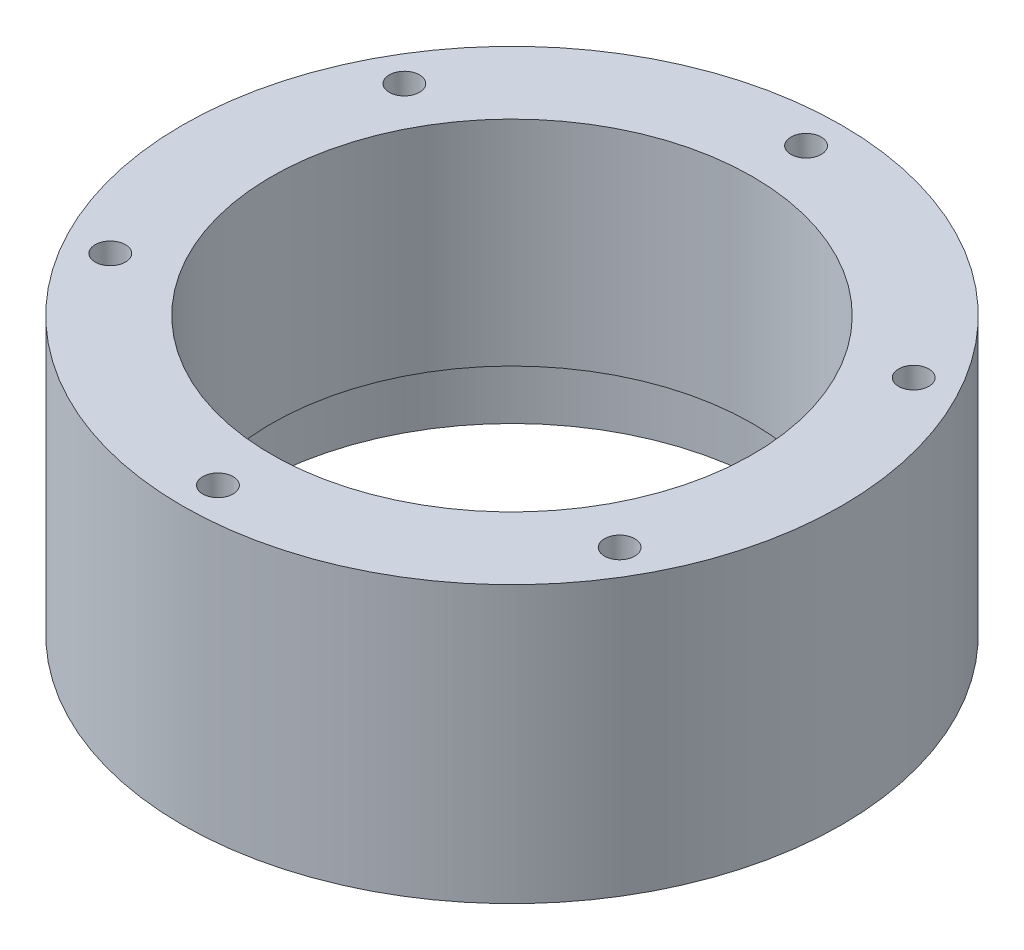
SolidWorks part; units mm, degrees
ref_plane "Ebene vorne" through (0, 0, 0) normal (0, 0, 1) x (1, 0, 0)
ref_plane "Ebene oben" through (0, 0, 0) normal (0, 1, 0) x (1, 0, 0)
ref_plane "Ebene rechts" through (0, 0, 0) normal (1, 0, 0) x (0, 0, -1)
sketch "Sketch1" plane through (0, 0, 0) normal (0, 0, 1) x (1, 0, 0)
  line L0 (0, 0) -> (0, 50) construction
  line L1 (29, 0) -> (37, 0)
  line L2 (37, 0) -> (37, 31)
  line L3 (37, 31) -> (27, 31)
  line L4 (27, 31) -> (27, 7)
  line L5 (27, 7) -> (29, 7)
  line L6 (29, 7) -> (29, 0)
  dimension "D1" = 50
  dimension "D2" = 58
  dimension "D3" = 2
  dimension "D4" = 24
  dimension "D5" = 7
  dimension "D6" = 8
revolve "Revolve1" add sketch "Sketch1" angle 360 about L0
hole_wizard "CBORE for M3 Hex Socket Head Cap Screw1" positions "Sketch2" profile "Sketch3" counterbore size "M3" standard "DIN" end condition through all
sketch "Sketch2" plane through (0, 0, 0) normal (0, -1, 0) x (-1, 0, 0)
  line L0 (0, -29) -> (0, -37) construction
  circle A0 centre (0, 0) radius 29 construction
  circle A1 centre (0, 0) radius 29 construction
  circle A2 centre (0, 0) radius 37 construction
  point P12 (0, -33)
  point P22 (-28.5788, -16.5)
  point P23 (-28.5788, 16.5)
  point P24 (0, 33)
  point P25 (28.5788, 16.5)
  point P26 (28.5788, -16.5)
  dimension "D1" = 6
sketch "Sketch3" plane through (-28.5788, 0, 16.5) normal (1, 0, 0) x (0, 0, -1)
  line L0 (0, 0) -> (0, 31)
  line L1 (0, 31) -> (1.7, 31)
  line L3 (1.7, 31) -> (1.7, 3.4)
  line L4 (1.7, 3.4) -> (3.25, 3.4)
  line L5 (3.25, 3.4) -> (3.25, 0)
  line L7 (3.25, 0) -> (0, 0)
  line L11 (0, -6.35) -> (0, 107.95) construction
  dimension "Thru Hole Dia." = 3.4
  dimension "Thru Hole Depth" = 31
  dimension "C'Bore Dia." = 6.5
  dimension "C'Bore Depth" = 3.4
